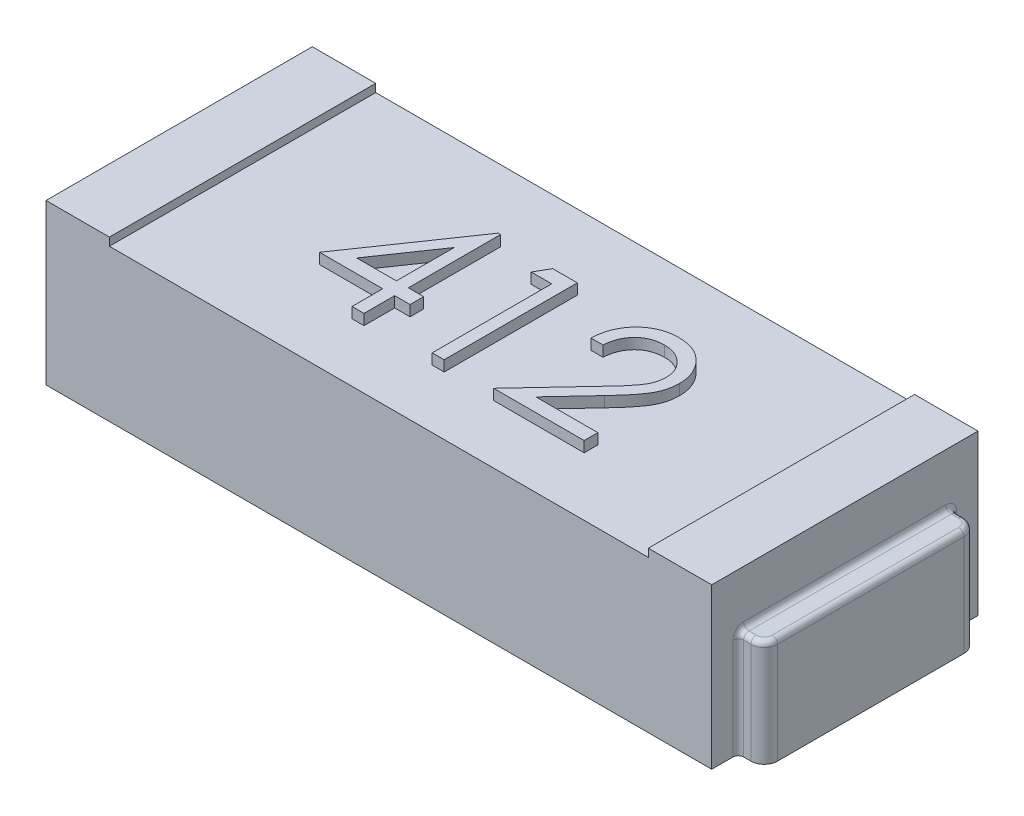
SolidWorks part; units mm, degrees
ref_plane "Plan de face" through (0, 0, 0) normal (0, 0, 1) x (1, 0, 0)
ref_plane "Plan de dessus" through (0, 0, 0) normal (0, 1, 0) x (1, 0, 0)
ref_plane "Plan de droite" through (0, 0, 0) normal (1, 0, 0) x (0, 0, -1)
sketch "Esquisse1" plane through (0, 0, 0) normal (0, 1, 0) x (1, 0, 0)
  line L1 (1.25, -0.5) -> (-1.25, -0.5)
  line L2 (1.25, -0.5) -> (1.25, 0.5)
  line L3 (1.25, 0.5) -> (-1.25, 0.5)
  line L4 (-1.25, -0.5) -> (-1.25, 0.5)
  line L5 (1.25, -0.5) -> (-1.25, 0.5) construction
  line L6 (1.25, 0.5) -> (-1.25, -0.5) construction
  point P0 (0, 0)
  dimension "D1" = 2.5
  dimension "D2" = 1
extrude "Boss.-Extru.1" add sketch "Esquisse1" along normal blind 0.6
sketch "Esquisse2" plane through (0, 0.6, 0) normal (0, 1, 0) x (1, 0, 0)
  line L0 (1.25, 0.5) -> (-1.25, 0.5) construction
  line L1 (1.0118, -0.5) -> (-1.0118, -0.5)
  line L2 (1.0118, -0.5) -> (1.0118, 0.5)
  line L3 (1.0118, 0.5) -> (-1.0118, 0.5)
  line L4 (-1.0118, -0.5) -> (-1.0118, 0.5)
  line L5 (1.0118, -0.5) -> (-1.0118, 0.5) construction
  line L6 (1.0118, 0.5) -> (-1.0118, -0.5) construction
  point P0 (0, 0)
extrude "Enlèv. mat.-Extru.1" cut sketch "Esquisse2" against normal blind 0.03
sketch "Esquisse3" plane through (0, 0, 0) normal (0, 1, 0) x (1, 0, 0)
  line L0 (1.25, -0.5) -> (1.25, 0.5) construction
  line L1 (1.25, 0.4) -> (1.2971, 0.4)
  line L2 (1.25, 0.4) -> (1.25, -0.4)
  line L3 (1.25, -0.4) -> (1.2971, -0.4)
  line L4 (1.3471, 0.35) -> (1.3471, -0.35)
  line L5 (1.25, 0.5) -> (1.0118, 0.5) construction
  line L6 (1.0118, -0.5) -> (1.25, -0.5) construction
  arc A0 (1.2971, -0.4) -> (1.3471, -0.35) centre (1.2971, -0.35) ccw
  arc A1 (1.2971, 0.4) -> (1.3471, 0.35) centre (1.2971, 0.35) cw
  dimension "D1" = 0.05
  dimension "D2" = 0.1
  dimension "D3" = 0.1
extrude "Boss.-Extru.2" add sketch "Esquisse3" along normal blind 0.4
fillet "Congé1" radius 0.02 8 edges at (1.25, 0.2, -0.4) (1.25, 0.2, 0.4) (1.2736, 0.4, -0.4) (1.3325, 0.4, -0.3854) (1.3471, 0.4, 0) (1.3325, 0.4, 0.3854) (1.2736, 0.4, 0.4) (1.25, 0.4, 0)
mirror "Symétrie2" about plane through (0, 0, 0) normal (1, 0, 0) of "Congé1", "Boss.-Extru.2"
sketch "Esquisse4" plane through (0, 0.57, 0) normal (0, 1, 0) x (1, 0, 0)
  line L0 (0.7576, -0.2803) -> (-0.7576, -0.2803) construction
  text T0 "412" font "Century Gothic" height 0.5
  point P3 (0, -0.2803)
extrude "Boss.-Extru.3" add sketch "Esquisse4" along normal blind 0.04
